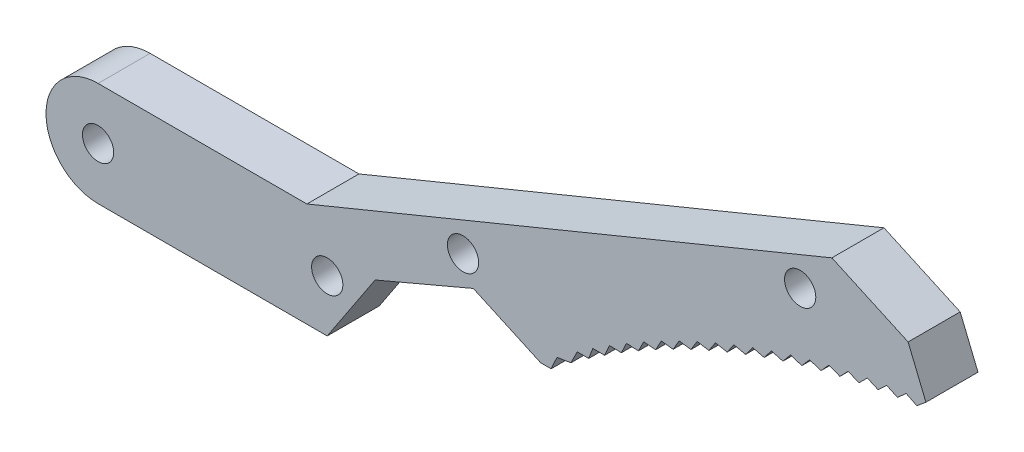
SolidWorks part; units mm, degrees
material "아크릴(내충격성)"
ref_plane "정면" through (0, 0, 0) normal (0, 0, 1) x (1, 0, 0)
ref_plane "윗면" through (0, 0, 0) normal (0, 1, 0) x (1, 0, 0)
ref_plane "우측면" through (0, 0, 0) normal (1, 0, 0) x (0, 0, -1)
sketch "스케치1" plane through (0, 0, 0) normal (0, 0, 1) x (1, 0, 0)
  line L0 (0, 0) -> (22, 0) construction
  line L1 (0, 5) -> (22, 5)
  line L2 (0, -5) -> (22, -5)
  line L7 (20.05, 5) -> (23.9914, -4.5863) construction
  line L8 (20.05, 5) -> (75.5427, 27.8158) construction
  line L9 (23.9914, -4.5863) -> (79.4841, 18.2295) construction
  line L10 (75.5427, 27.8158) -> (79.4841, 18.2295) construction
  line L11 (20.05, 5) -> (70.4559, 25.7244)
  line L12 (70.4559, 25.7244) -> (77.7729, 22.3914)
  line L13 (77.7729, 22.3914) -> (79.4841, 18.2295)
  line L14 (42.489, 3.019) -> (43.4982, 3.019)
  line L15 (42.489, 3.019) -> (36.0251, 5.9632)
  line L16 (36.0251, 5.9632) -> (26.6014, 1.9564)
  line L17 (43.4982, 3.019) -> (44.0621, 4.2539)
  line L18 (44.0621, 4.2539) -> (45.4024, 4.4704)
  line L19 (45.4024, 4.4704) -> (46.0087, 5.6852)
  line L20 (46.0087, 5.6852) -> (47.1079, 5.6852)
  line L21 (47.1079, 5.6852) -> (47.4984, 6.7127)
  line L22 (47.4984, 6.7127) -> (48.641, 6.7127)
  line L23 (48.641, 6.7127) -> (49.103, 7.7576)
  line L24 (49.103, 7.7576) -> (50.2451, 7.7264)
  line L25 (50.2451, 7.7264) -> (50.7356, 8.7582)
  line L26 (50.7356, 8.7582) -> (51.8764, 8.6958)
  line L27 (51.8764, 8.6958) -> (52.3949, 9.7138)
  line L28 (26.6014, 1.9564) -> (22, -5)
  line L29 (52.3949, 9.7138) -> (53.5336, 9.6202)
  line L30 (53.5336, 9.6202) -> (54.0798, 10.6237)
  line L31 (54.0798, 10.6237) -> (55.2154, 10.4989)
  line L32 (55.2154, 10.4989) -> (55.7889, 11.4871)
  line L33 (55.7889, 11.4871) -> (56.9207, 11.3313)
  line L34 (19.8104, 5.5827) -> (70.4687, 26.4108) construction
  line L35 (70.4687, 26.4108) -> (78.2608, 22.8615) construction
  line L36 (78.2608, 22.8615) -> (80.3902, 17.6823) construction
  line L37 (56.9207, 11.3313) -> (57.5209, 12.3034)
  line L38 (57.5209, 12.3034) -> (58.6481, 12.1167)
  line L39 (58.6481, 12.1167) -> (59.2747, 13.0721)
  line L40 (59.2747, 13.0721) -> (60.3963, 12.8546)
  line L41 (60.3963, 12.8546) -> (61.0488, 13.7925)
  line L42 (61.0488, 13.7925) -> (62.1641, 13.5444)
  line L43 (62.1641, 13.5444) -> (62.842, 14.4641)
  line L44 (62.842, 14.4641) -> (63.95, 14.1857)
  line L45 (63.95, 14.1857) -> (64.6528, 15.0864)
  line L46 (64.6528, 15.0864) -> (65.7529, 14.7778)
  line L47 (65.7529, 14.7778) -> (66.4801, 15.659)
  line L48 (66.4801, 15.659) -> (67.5712, 15.3203)
  line L49 (67.5712, 15.3203) -> (68.3222, 16.1813)
  line L50 (68.3222, 16.1813) -> (69.4037, 15.813)
  line L51 (69.4037, 15.813) -> (70.1655, 16.6501)
  line L52 (70.1655, 16.6501) -> (71.2242, 16.2497)
  line L53 (71.2242, 16.2497) -> (72.0083, 17.066)
  line L54 (72.0083, 17.066) -> (73.0558, 16.6372)
  line L55 (73.0558, 16.6372) -> (73.8616, 17.432)
  line L56 (73.8616, 17.432) -> (74.8971, 16.9751)
  line L57 (74.8971, 16.9751) -> (75.7241, 17.7478)
  line L58 (75.7241, 17.7478) -> (76.7469, 17.2631)
  line L59 (76.7469, 17.2631) -> (77.5945, 18.0133)
  line L60 (77.5945, 18.0133) -> (78.6038, 17.5012)
  line L61 (78.6038, 17.5012) -> (79.4841, 18.2295)
  line L62 (36.0251, 5.9632) -> (34.0539, 10.7577)
  arc A0 (0, 5) -> (0, -5) centre (0, 0) ccw
  arc A1 (22, -5) -> (22, 5) centre (22, 0) ccw
  circle A2 centre (22, 0) radius 1.5
  circle A3 centre (0, 0) radius 1.5
  arc A4 (42.489, 3.019) -> (79.4841, 18.2295) centre (86.4954, -51.4185) cw
  arc A5 (42.885, 2.529) -> (80.3902, 17.6823) centre (86.4954, -51.4185) cw construction
  circle A6 centre (35.0395, 8.3605) radius 1.5
  circle A7 centre (67.4103, 21.6697) radius 1.5
  point P3 (11, 0)
  dimension "D2" = 10
  dimension "D10" = 3
  dimension "D7" = 70
  dimension "D1" = 22
  dimension "D3" = 157.65
  dimension "D4" = 1.95
  dimension "D5" = 60
  dimension "D6" = 40
  dimension "D8" = 4.5
  dimension "D9" = 5.5
  dimension "D11" = 10.2402
  dimension "D12" = 2
  dimension "D13" = 0.63
extrude "보스-돌출1" add sketch "스케치1" along normal blind 5
